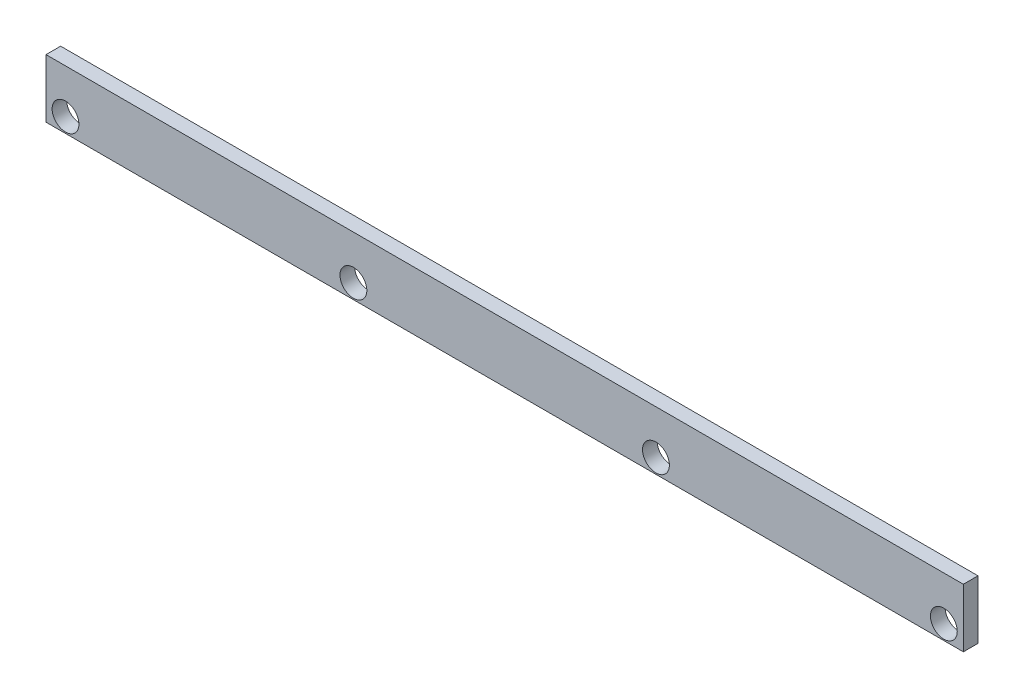
SolidWorks part; units mm, degrees
ref_plane "Front Plane" through (0, 0, 0) normal (0, 0, 1) x (1, 0, 0)
ref_plane "Top Plane" through (0, 0, 0) normal (0, 1, 0) x (1, 0, 0)
ref_plane "Right Plane" through (0, 0, 0) normal (1, 0, 0) x (0, 0, -1)
sketch "Floor joint holes profile" plane through (0, 0, 0) normal (0, 0, 1) x (1, 0, 0)
  line L0 (-94, -12) -> (94, -12)
  line L1 (94, -12) -> (94, 0)
  line L2 (94, 0) -> (-94, 0)
  line L3 (-94, 0) -> (-94, -12)
  circle A0 centre (-90, -9) radius 2.75
  circle A1 centre (-31, -9) radius 2.75
  circle A2 centre (31, -9) radius 2.75
  circle A3 centre (90, -9) radius 2.75
extrude "Floor joint holes" add sketch "Floor joint holes profile" along normal blind 3
